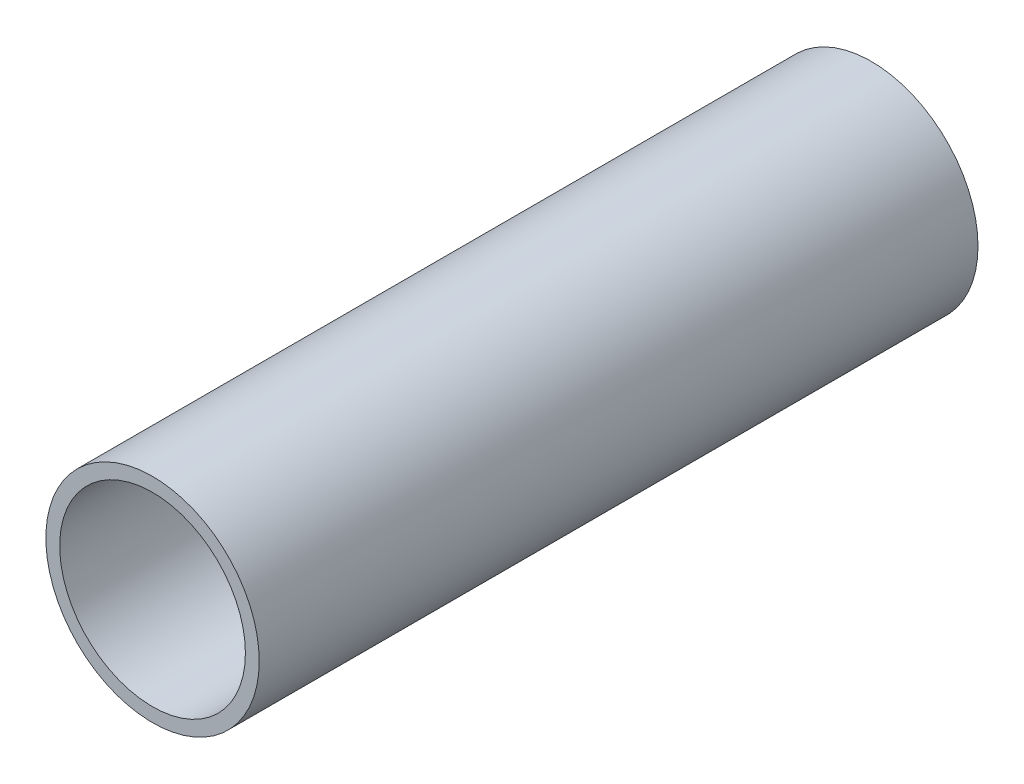
SolidWorks part; units mm, degrees
material "ABS"
ref_plane "Front Plane" through (0, 0, 0) normal (0, 0, 1) x (1, 0, 0)
ref_plane "Top Plane" through (0, 0, 0) normal (0, 1, 0) x (1, 0, 0)
ref_plane "Right Plane" through (0, 0, 0) normal (1, 0, 0) x (0, 0, -1)
sketch "Sketch1" plane through (0, 0, 0) normal (0, 0, 1) x (1, 0, 0)
  circle A0 centre (0, 0) radius 30.1625
  dimension "Pipe OD" = 60.325
extrude "Extrude-Thin1" add sketch "Sketch1" along normal mid plane 203.2 thin thin type one direction reverse wall 3.9116
